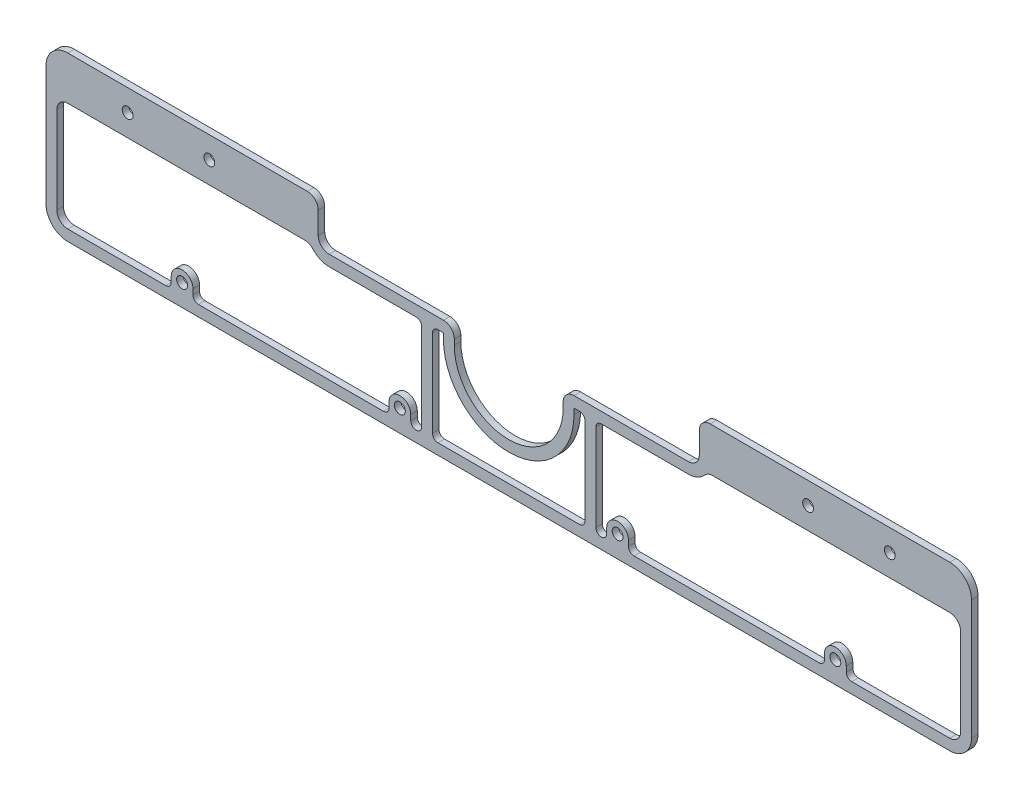
SolidWorks part; units mm, degrees
ref_plane "Front Plane" through (0, 0, 0) normal (0, 0, 1) x (1, 0, 0)
ref_plane "Top Plane" through (0, 0, 0) normal (0, 1, 0) x (1, 0, 0)
ref_plane "Right Plane" through (0, 0, 0) normal (1, 0, 0) x (0, 0, -1)
sketch "Sketch1" plane through (0, 0, 0) normal (0, 0, 1) x (1, 0, 0)
  line L0 (-50, 0) -> (-50, 35) construction
  line L1 (405, -95) -> (-405, -95) construction
  line L4 (-425, -75) -> (-425, 35)
  line L8 (-60, 55) -> (-405, 55) construction
  line L21 (-165.0003, 15) -> (-60, 15)
  line L25 (0, -50) -> (0, -95)
  line L26 (0, 55) -> (0, -95) construction
  line L27 (-50, 75) -> (50, 75) construction
  line L32 (-50, 5) -> (-50, 0)
  line L34 (0, -95) -> (-405, -95)
  line L170 (-405, 55) -> (-185.0003, 55)
  line L175 (-175.0003, 45) -> (-175.0003, 25)
  circle A1 centre (0, 0) radius 30 construction
  arc A4 (-405, -95) -> (-425, -75) centre (-405, -75) cw
  arc A5 (-425, 35) -> (-405, 55) centre (-405, 35) cw
  circle A26 centre (-350, 35) radius 5
  circle A27 centre (-275, 35) radius 5
  arc A136 (-50, 0) -> (0, -50) centre (0, 0) ccw
  arc A137 (-50, 5) -> (-60, 15) centre (-60, 5) ccw
  arc A138 (-165.0003, 15) -> (-175.0003, 25) centre (-165.0003, 25) cw
  arc A139 (-175.0003, 45) -> (-185.0003, 55) centre (-185.0003, 45) ccw
  point P11 (0, 30)
  point P15 (-50, 15)
  point P27 (-175.0003, 55)
  point P30 (-50, 55)
  point P74 (0, 75)
  dimension "D3" = 10
  dimension "D4" = 60
  dimension "D6" = 55
  dimension "D7" = 425
  dimension "D10" = 175.0003
  dimension "D11" = 20
  dimension "D12" = 50
  dimension "D20" = 10
  dimension "D21" = 10
  dimension "D5" = 150
  dimension "D9" = 40
  dimension "D16" = 100
  dimension "D17" = 20
  dimension "D18" = 375
  dimension "D19" = 20
  dimension "D22" = 20
  dimension "D23" = 75
  dimension "D24" = 225
  dimension "D8" = 345
extrude "Boss-Extrude1" add sketch "Sketch1" along normal blind 6
mirror "Mirror1" about plane through (0, -50, 6) normal (-1, 0, 0) of "Boss-Extrude1"
sketch "Sketch2" plane through (0, 0, 6) normal (0, 0, 1) x (1, 0, 0)
  line L0 (0, -29.253) -> (0, -89.121) construction
  line L1 (-185.0003, 55) -> (-405, 55) construction
  line L3 (-290, -75) -> (-290, -80)
  line L4 (-310, -75) -> (-310, -80)
  line L5 (-110, -75) -> (-110, -80)
  line L6 (-90, -75) -> (-90, -80)
  line L7 (-405, -85) -> (-315, -85)
  line L8 (-285, -85) -> (-115, -85)
  line L52 (-405, 15) -> (-187.361, 15)
  line L55 (-185.0003, 45) -> (-405, 45)
  line L56 (-185.0003, 25) -> (-185.0003, 45)
  line L57 (-60, 0) -> (-60, 5)
  line L58 (-60, 5) -> (-165.0003, 5)
  line L59 (-415, 35) -> (-415, -75)
  line L60 (-405, -85) -> (405, -85)
  line L61 (-185.0003, 45) -> (-405, 45) construction
  line L62 (-185.0003, 25) -> (-185.0003, 45) construction
  line L63 (-60, 0) -> (-60, 5)
  line L64 (-85, 5) -> (-165.0003, 5)
  line L65 (-415, 35) -> (-415, -75) construction
  line L66 (-405, -85) -> (-85, -85) construction
  line L67 (0, -60) -> (0, -85)
  line L68 (-415, 5) -> (-415, -75)
  line L69 (-80, 0) -> (-80, -80)
  line L70 (-70, 0) -> (-70, -80)
  line L71 (-65, 5) -> (-60, 5)
  line L72 (-65, -85) -> (0, -85)
  arc A4 (-65, -85) -> (-70, -80) centre (-65, -80) cw
  arc A5 (-70, 0) -> (-65, 5) centre (-65, 0) cw
  arc A6 (-165.0003, 5) -> (-179.9075, 11.6667) centre (-165.0003, 25) cw
  arc A7 (-179.9075, 11.6667) -> (-187.361, 15) centre (-187.361, 5) ccw
  arc A8 (-415, 5) -> (-405, 15) centre (-405, 5) cw
  circle A9 centre (-300, -75) radius 5
  circle A10 centre (-100, -75) radius 5
  arc A11 (-90, -75) -> (-110, -75) centre (-100, -75) ccw
  arc A12 (-290, -75) -> (-310, -75) centre (-300, -75) ccw
  arc A13 (-285, -85) -> (-290, -80) centre (-285, -80) cw
  arc A14 (-315, -85) -> (-310, -80) centre (-315, -80) ccw
  arc A15 (-115, -85) -> (-110, -80) centre (-115, -80) ccw
  arc A16 (-90, -80) -> (-85, -85) centre (-85, -80) ccw
  arc A43 (-80, 0) -> (-85, 5) centre (-85, 0) ccw
  arc A44 (-85, -85) -> (-80, -80) centre (-85, -80) ccw
  arc A49 (-405, 45) -> (-415, 35) centre (-405, 35) ccw
  arc A50 (-185.0003, 25) -> (-165.0003, 5) centre (-165.0003, 25) ccw
  arc A51 (-60, 0) -> (60, 0) centre (0, 0) ccw
  arc A52 (-415, -75) -> (-405, -85) centre (-405, -75) ccw
  arc A53 (-405, 45) -> (-415, 35) centre (-405, 35) ccw construction
  arc A54 (-185.0003, 25) -> (-165.0003, 5) centre (-165.0003, 25) ccw construction
  arc A55 (-60, 0) -> (0, -60) centre (0, 0) ccw
  arc A56 (-415, -75) -> (-405, -85) centre (-405, -75) ccw
  point P12 (-415, 15)
  point P29 (-300, -85)
  point P34 (-70, -85)
  point P37 (-70, 5)
  point P45 (-290, -85)
  point P48 (-310, -85)
  point P51 (-110, -85)
  point P54 (-90, -85)
  dimension "D3" = 10
  dimension "D9" = 5
  dimension "D10" = 5
  dimension "D11" = 300
  dimension "D12" = 5
  dimension "D4" = 10
  dimension "D5" = 20
  dimension "D14" = 5
  dimension "D2" = 40
  dimension "D7" = 20
  dimension "D8" = 10
  dimension "D13" = 100
  dimension "D6" = 10
extrude "Cut-Extrude1" cut sketch "Sketch2" against normal through all
mirror "Mirror2" about plane through (0, 0, 0) normal (1, 0, 0) of "Cut-Extrude1"
